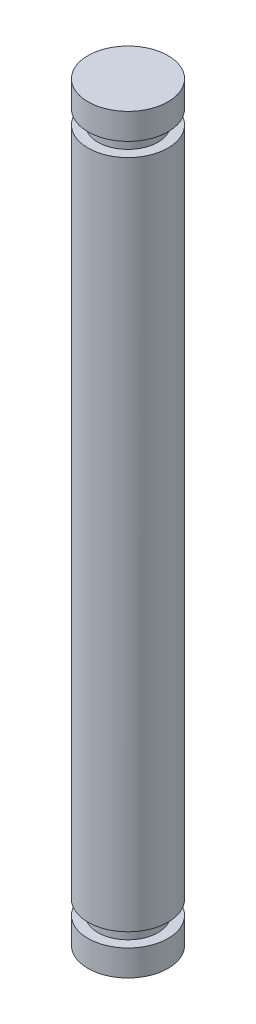
SolidWorks part; units mm, degrees
ref_plane "정면" through (0, 0, 0) normal (0, 0, 1) x (1, 0, 0)
ref_plane "윗면" through (0, 0, 0) normal (0, 1, 0) x (1, 0, 0)
ref_plane "우측면" through (0, 0, 0) normal (1, 0, 0) x (0, 0, -1)
sketch "스케치1" plane through (0, 0, 0) normal (0, 1, 0) x (1, 0, 0)
  circle A0 centre (0, 0) radius 2
  dimension "D1" = 4
extrude "보스-돌출1" add sketch "스케치1" along normal blind 37.5
sketch "스케치2" plane through (0, 37.5, 0) normal (0, 1, 0) x (1, 0, 0)
  circle A0 centre (0, 0) radius 2
  circle A1 centre (0, 0) radius 1.5
  dimension "D1" = 3
extrude "컷-돌출1" cut sketch "스케치2" against normal blind 0.7 from offset 1.3 offset against normal yes
sketch "스케치3" plane through (0, 0, 0) normal (0, -1, 0) x (1, 0, 0)
  circle A0 centre (0, 0) radius 2
  circle A1 centre (0, 0) radius 1.5
  dimension "D1" = 3
extrude "컷-돌출2" cut sketch "스케치3" against normal blind 0.7 from offset 1.3
